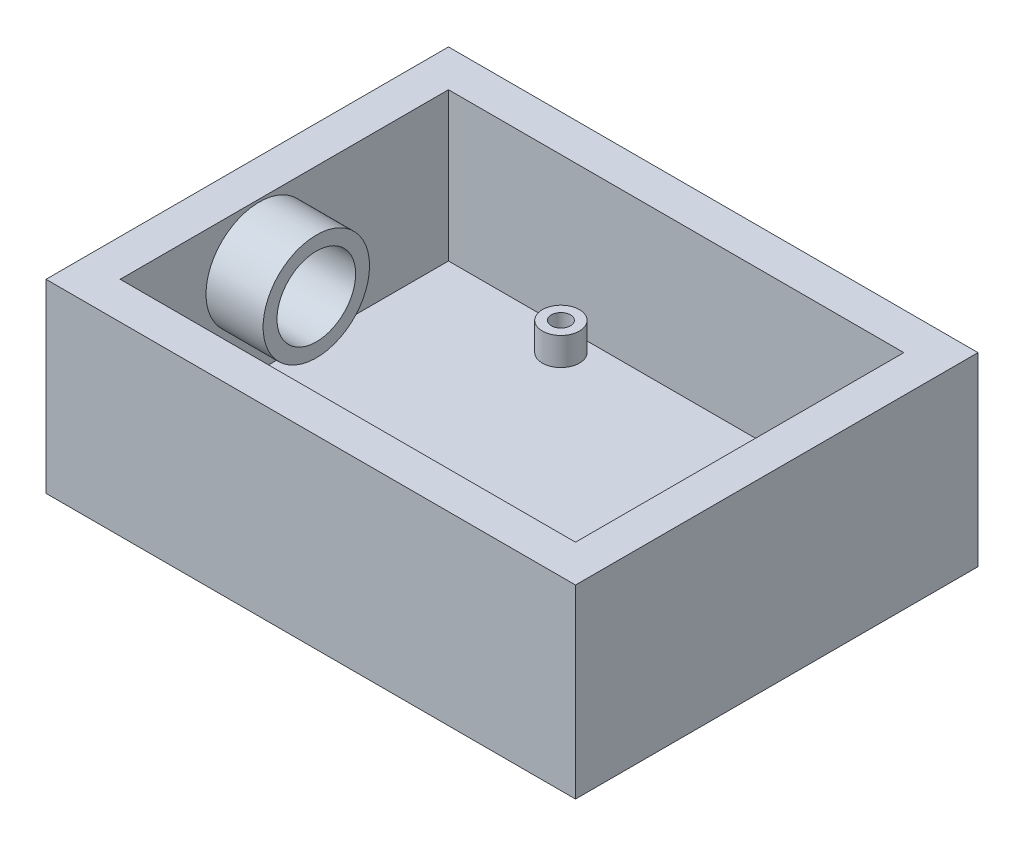
SolidWorks part; units mm, degrees
ref_plane "Front Plane" through (0, 0, 0) normal (0, 0, 1) x (1, 0, 0)
ref_plane "Top Plane" through (0, 0, 0) normal (0, 1, 0) x (1, 0, 0)
ref_plane "Right Plane" through (0, 0, 0) normal (1, 0, 0) x (0, 0, -1)
ref_plane "Plane1" through (0, 34.3612, 0) normal (0, -1, 0) x (-1, 0, 0)
sketch "Sketch1" plane through (0, 34.3612, 0) normal (0, -1, 0) x (-1, 0, 0)
  line L0 (-20.2485, -29.9621) -> (-20.2485, -31.5496) construction
  line L1 (-59.236, -29.9621) -> (18.739, -29.9621) construction
  line L2 (-59.236, -29.9621) -> (-59.236, -86.1871) construction
  line L3 (-59.236, -86.1871) -> (18.739, -86.1871) construction
  line L4 (18.739, -29.9621) -> (18.739, -86.1871) construction
  line L5 (-59.236, -58.0746) -> (-57.6485, -58.0746) construction
  line L6 (-20.2485, -86.1871) -> (-20.2485, -84.5996) construction
  line L7 (18.739, -58.0746) -> (17.1515, -58.0746) construction
  line L8 (-55.1485, -31.5496) -> (9.8515, -31.5496) construction
  line L9 (-57.6485, -79.7996) -> (-57.6485, -46.8996) construction
  line L10 (9.8515, -84.5996) -> (-54.4485, -84.5996) construction
  line L11 (17.1515, -52.3496) -> (17.1515, -40.5496) construction
  line L12 (-65.586, -58.0746) -> (-59.236, -58.0746) construction
  line L13 (-65.586, -23.6121) -> (25.089, -23.6121) construction
  line L14 (-65.586, -23.6121) -> (-65.586, -92.5371) construction
  line L15 (-65.586, -92.5371) -> (25.089, -92.5371) construction
  line L16 (25.089, -23.6121) -> (25.089, -92.5371) construction
  line L17 (-20.2485, -23.6121) -> (-20.2485, -29.9621) construction
  line L18 (25.089, -58.0746) -> (18.739, -58.0746) construction
  line L19 (-20.2485, -92.5371) -> (-20.2485, -86.1871) construction
  circle A0 centre (-4.4485, -33.8996) radius 3.175 construction
  circle A1 centre (-55.2485, -49.0496) radius 3.175 construction
  circle A2 centre (-55.2485, -76.9996) radius 3.175 construction
  circle A3 centre (-3.0485, -82.1996) radius 3.175 construction
  point P12 (-4.4485, -33.8996)
  point P15 (-3.0485, -82.1996)
  point P18 (-55.2485, -76.9996)
  point P24 (-55.2485, -49.0496)
  dimension "D3" = 6.35
  dimension "D1" = 1.5875
  dimension "D2" = 6.35
sketch "Sketch2" plane through (0, 34.3612, 0) normal (0, -1, 0) x (-1, 0, 0)
  line L1 (-65.586, -23.6121) -> (25.089, -23.6121)
  line L2 (-65.586, -23.6121) -> (-65.586, -92.5371)
  line L3 (-65.586, -92.5371) -> (25.089, -92.5371)
  line L4 (25.089, -23.6121) -> (25.089, -92.5371)
extrude "Boss-Extrude1" add sketch "Sketch2" along normal blind 6.35
sketch "Sketch3" plane through (0, 34.3612, 0) normal (0, -1, 0) x (-1, 0, 0)
  circle A0 centre (-4.4485, -33.8996) radius 3.175
  circle A1 centre (-55.2485, -49.0496) radius 3.175
  circle A2 centre (-55.2485, -76.9996) radius 3.175
  circle A3 centre (-3.0485, -82.1996) radius 3.175
  circle A4 centre (-55.2485, -76.9996) radius 3.175 construction
  circle A5 centre (-55.2485, -49.0496) radius 3.175 construction
  circle A6 centre (-4.4485, -33.8996) radius 3.175 construction
  circle A7 centre (-3.0485, -82.1996) radius 3.175 construction
extrude "Boss-Extrude2" add sketch "Sketch3" against normal up to surface (4.7625 mm away)
hole_wizard "CSK for #4 Flat Head Machine Screw1" positions "Sketch7" profile "Sketch9" countersink size "#4" standard "ANSI Inch" end condition through all
sketch "Sketch7" plane through (0, 28.0112, 0) normal (0, -1, 0) x (-1, 0, 0)
  point P2 (-3.0485, -82.1996)
  point P5 (-55.2485, -76.9996)
  point P8 (-55.2485, -49.0496)
  point P11 (-4.4485, -33.8996)
  point P15 (0, 0)
sketch "Sketch9" plane through (3.0485, 28.0112, 82.1996) normal (1, 0, 0) x (0, 0, -1)
  line L0 (0, 0) -> (0, 11.1125)
  line L1 (0, 11.1125) -> (1.6319, 11.1125)
  line L2 (1.6319, 11.1125) -> (1.6319, 1.4098)
  line L3 (1.6319, 1.4098) -> (2.8575, 0)
  line L5 (2.8575, 0) -> (0, 0)
  line L6 (-1.6319, 1.4098) -> (-2.8575, 0) construction
  line L11 (0, -6.35) -> (0, 107.95) construction
  dimension "Thru Hole Dia." = 3.2639
  dimension "Thru Hole Depth" = 11.1125
  dimension "Near C'Sink Dia." = 5.715
  dimension "Near C'Sink Angle" = 82
sketch "Sketch10" plane through (0, 34.3612, 0) normal (0, 1, 0) x (1, 0, 0)
  line L1 (59.236, -29.9621) -> (-18.739, -29.9621)
  line L2 (59.236, -29.9621) -> (59.236, -86.1871)
  line L3 (59.236, -86.1871) -> (-18.739, -86.1871)
  line L4 (-18.739, -29.9621) -> (-18.739, -86.1871)
  line L5 (65.586, -23.6121) -> (-25.089, -23.6121)
  line L6 (65.586, -23.6121) -> (65.586, -92.5371)
  line L7 (65.586, -92.5371) -> (-25.089, -92.5371)
  line L8 (-25.089, -23.6121) -> (-25.089, -92.5371)
extrude "Boss-Extrude4" add sketch "Sketch10" along normal blind 25.4
sketch "Sketch11" plane through (-18.739, 0, 0) normal (1, 0, 0) x (0, 0, -1)
  line L0 (-86.1871, 40.6737) -> (-29.9621, 40.6737) construction
  line L1 (-86.1871, 59.7612) -> (-86.1871, 34.3612) construction
  line L2 (-29.9621, 59.7612) -> (-29.9621, 34.3612) construction
  line L5 (-29.9621, 59.7612) -> (-29.9621, 34.3612) construction
  line L6 (-62.3746, 50.1987) -> (-62.3746, 40.6737) construction
  line L7 (-32.2496, 40.6737) -> (-83.8996, 40.6737) construction
  line L10 (-86.1871, 50.1987) -> (-29.9621, 50.1987) construction
  circle A0 centre (-62.3746, 50.1987) radius 5.9373 construction
  circle A1 centre (-62.3746, 50.1987) radius 6.731
  circle A2 centre (-62.3746, 50.1987) radius 9.1123
  dimension "D1" = 11.8745
  dimension "D3" = 0.7937
  dimension "D2" = 2.3813
  dimension "D5" = 23.8125
  dimension "D6" = 9.525
extrude "Boss-Extrude5" add sketch "Sketch11" along normal blind 9.779
sketch "Sketch12" plane through (-25.089, 0, 0) normal (-1, 0, 0) x (0, 0, 1)
  circle A0 centre (62.3746, 50.1987) radius 1.5875
  dimension "D1" = 3.175
extrude "Cut-Extrude1" cut sketch "Sketch12" against normal up to next
